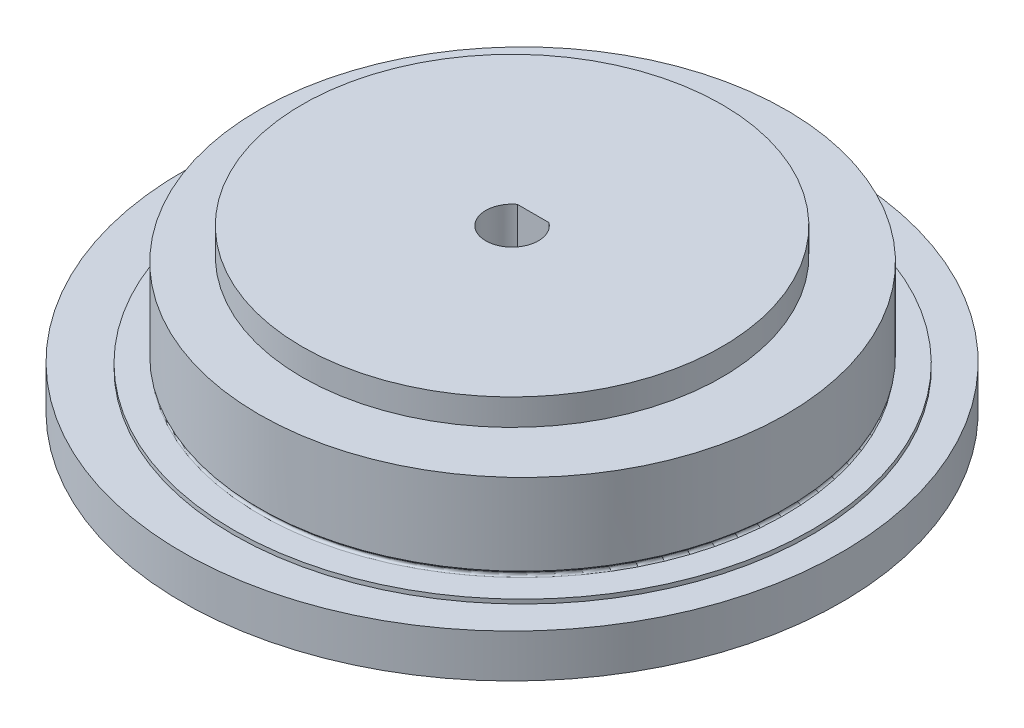
SolidWorks part; units mm, degrees
ref_plane "Front Plane" through (0, 0, 0) normal (0, 0, 1) x (1, 0, 0)
ref_plane "Top Plane" through (0, 0, 0) normal (0, 1, 0) x (1, 0, 0)
ref_plane "Right Plane" through (0, 0, 0) normal (1, 0, 0) x (0, 0, -1)
sketch "Sketch1" plane through (0, 0, 0) normal (0, 1, 0) x (1, 0, 0)
  line L1 (-2.5, 2) -> (0.5, 2)
  circle A0 centre (0, 0) radius 25
  arc A2 (-2.5, 2) -> (0.5, 2) centre (-1, 0) ccw
  point P7 (-1, -2.5)
  dimension "D1" = 5
  dimension "D2" = 50
  dimension "D3" = 1
  dimension "D4" = 4.5
extrude "Boss-Extrude1" add sketch "Sketch1" along normal blind 10.8
sketch "Sketch2" plane through (0, 0, 0) normal (0, -1, 0) x (1, 0, 0)
  line L0 (0.5, -2) -> (-2.5, -2) construction
  line L1 (0.5, -2) -> (-2.5, -2)
  circle A0 centre (-1, 0) radius 31.25
  circle A3 centre (-1, 0) radius 2.5 construction
  arc A4 (0.5, -2) -> (-2.5, -2) centre (-1, 0) ccw
  dimension "D1" = 62.5
extrude "Boss-Extrude2" add sketch "Sketch2" along normal blind 2
sketch "Sketch3" plane through (0, -2, 0) normal (0, -1, 0) x (1, 0, 0)
  line L0 (-2.5, -2) -> (0.5, -2) construction
  line L1 (-2.5, -2) -> (0.5, -2)
  circle A0 centre (-1, 0) radius 31.25 construction
  circle A1 centre (-1, 0) radius 31.25
  circle A2 centre (-1, 0) radius 30.1
  circle A3 centre (-1, 0) radius 19.9
  circle A6 centre (-1, 0) radius 2.5 construction
  arc A7 (0.5, -2) -> (-2.5, -2) centre (-1, 0) ccw
  dimension "D2" = 39.8
  dimension "D1" = 60.2
extrude "Boss-Extrude3" add sketch "Sketch3" along normal blind 2.5
sketch "Sketch4" plane through (0, 0, 0) normal (0, 1, 0) x (1, 0, 0)
  circle A0 centre (0, 0) radius 25 construction
  circle A1 centre (0, 0) radius 25 construction
  circle A2 centre (0, 0) radius 27.4
  circle A3 centre (-1, 0) radius 31.25 construction
  circle A4 centre (-1, 0) radius 31.25
  dimension "D1" = 2.4
extrude "Cut-Extrude1" cut sketch "Sketch4" against normal blind 0.4
sketch "Sketch5" plane through (0, 10.8, 0) normal (0, 1, 0) x (1, 0, 0)
  circle A0 centre (-1, 0) radius 19.9
  circle A1 centre (0, 0) radius 25 construction
  circle A2 centre (0, 0) radius 25
  dimension "D1" = 39.8
extrude "Cut-Extrude2" cut sketch "Sketch5" against normal blind 2.5
sketch "Sketch6" plane through (0, 0, 0) normal (0, 0, 1) x (1, 0, 0)
  line L0 (-25, 0) -> (-25, 0.6)
  line L1 (25, 0) -> (-25, 0) construction
  line L2 (27.4, 0) -> (-27.4, 0) construction
  line L3 (-25, 0.6) -> (-24.4, 0)
  line L4 (-24.4, 0) -> (-25, 0)
  dimension "D1" = 0.6
ref_axis "Axis1" through (0, 8.3, 0) along (0, -1, 0)
revolve "Cut-Revolve1" cut sketch "Sketch6" angle 360 about axis through (0, 8.3, 0) along (0, -1, 0)
fillet "Fillet1" radius 0.2 1 edges at (0, 0, 24.4)
ref_plane "Plane1" through (0, 0, -25) normal (0, 0, -1) x (-1, 0, 0)
sketch "Sketch7" plane through (0, 0, -25) normal (0, 0, -1) x (-1, 0, 0)
  line L0 (1, 10.8) -> (1, 3.15) construction
  line L4 (2.5, -4.5) -> (2.5, 10.8)
  line L5 (-0.5, -4.5) -> (2.5, -4.5)
  line L6 (-0.5, 10.8) -> (-0.5, -4.5)
  line L7 (2.5, 10.8) -> (-0.5, 10.8)
  line L8 (2.5, -4.5) -> (2.5, 10.8) construction
  line L9 (-0.5, -4.5) -> (2.5, -4.5) construction
  line L10 (-0.5, 10.8) -> (-0.5, -4.5) construction
  line L11 (2.5, 10.8) -> (-0.5, 10.8) construction
  circle A0 centre (1, 3.15) radius 2.15
  dimension "D2" = 4.3
  dimension "D1" = 0
extrude "Cut-Extrude3" cut sketch "Sketch7" against normal up to next (23 mm away) and the other way through all
sketch "Sketch8" plane through (0, 0, -25) normal (0, 0, -1) x (-1, 0, 0)
  circle A2 centre (1, 3.15) radius 4.15
  circle A3 centre (1, 3.15) radius 4.15
  dimension "D1" = 2
extrude "Cut-Extrude4" cut sketch "Sketch8" against normal blind 16 and the other way through all
